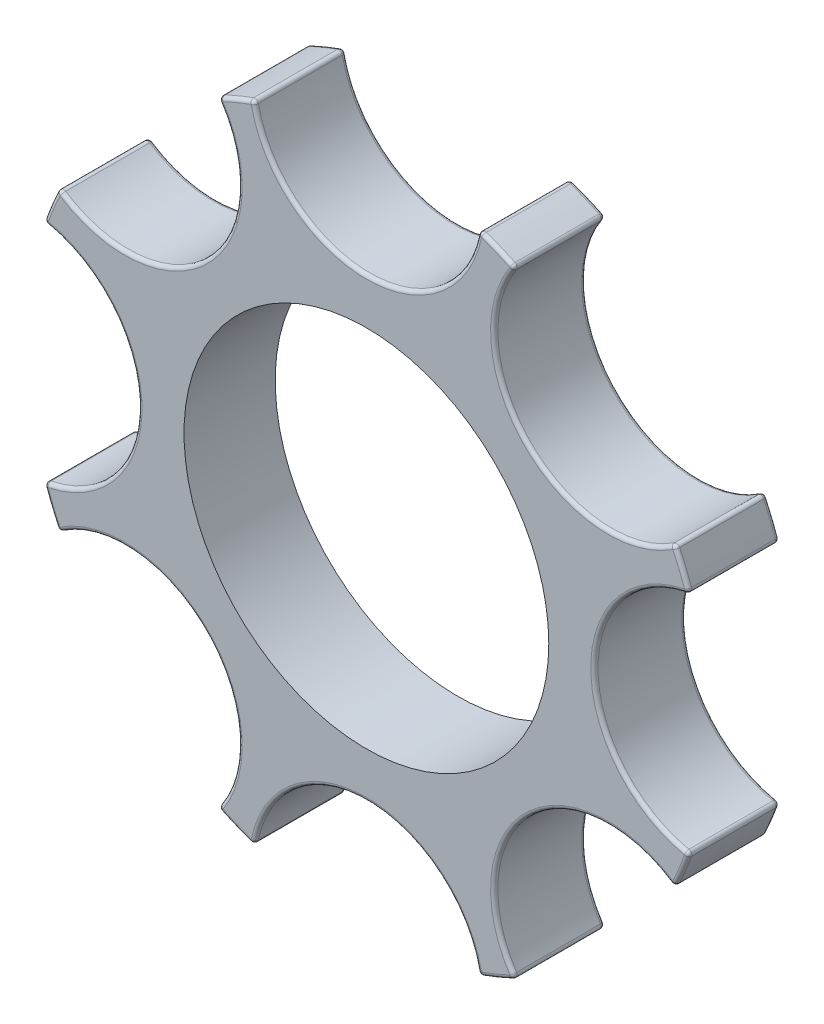
SolidWorks part; units mm, degrees
material "Plain Carbon Steel"
ref_plane "Front Plane" through (0, 0, 0) normal (0, 0, 1) x (1, 0, 0)
ref_plane "Top Plane" through (0, 0, 0) normal (0, 1, 0) x (1, 0, 0)
ref_plane "Right Plane" through (0, 0, 0) normal (1, 0, 0) x (0, 0, -1)
sketch "Sketch1" plane through (0, 0, 0) normal (0, 0, 1) x (1, 0, 0)
  circle A0 centre (0, 0) radius 10.16
  arc A1 (-17.1494, 8.2947) -> (-17.9917, 6.2612) centre (0, 0) ccw
  arc A2 (-6.2612, 17.9917) -> (6.2612, 17.9917) centre (0, 19.05) ccw
  arc A3 (-17.1494, 8.2947) -> (-17.9917, 6.2612) centre (0, 0) ccw
  arc A4 (8.2947, 17.1494) -> (17.1494, 8.2947) centre (13.4704, 13.4704) ccw
  arc A5 (-17.1494, 8.2947) -> (-17.9917, 6.2612) centre (0, 0) ccw
  arc A6 (17.9917, 6.2612) -> (17.9917, -6.2612) centre (19.05, 0) ccw
  arc A7 (-17.1494, 8.2947) -> (-17.9917, 6.2612) centre (0, 0) ccw
  arc A8 (17.1494, -8.2947) -> (8.2947, -17.1494) centre (13.4704, -13.4704) ccw
  arc A9 (-17.1494, 8.2947) -> (-17.9917, 6.2612) centre (0, 0) ccw
  arc A10 (6.2612, -17.9917) -> (-6.2612, -17.9917) centre (0, -19.05) ccw
  arc A11 (-17.1494, 8.2947) -> (-17.9917, 6.2612) centre (0, 0) ccw
  arc A12 (-8.2947, -17.1494) -> (-17.1494, -8.2947) centre (-13.4704, -13.4704) ccw
  arc A13 (-17.1494, 8.2947) -> (-17.9917, 6.2612) centre (0, 0) ccw
  arc A14 (-17.9917, -6.2612) -> (-17.9917, 6.2612) centre (-19.05, 0) ccw
  arc A15 (-17.1494, 8.2947) -> (-17.9917, 6.2612) centre (0, 0) ccw
  arc A16 (-17.1494, 8.2947) -> (-8.2947, 17.1494) centre (-13.4704, 13.4704) ccw
  arc A17 (-6.2612, 17.9917) -> (-8.2947, 17.1494) centre (0, 0) ccw
  arc A18 (-6.2612, 17.9917) -> (-8.2947, 17.1494) centre (0, 0) ccw
  arc A19 (-6.2612, 17.9917) -> (-8.2947, 17.1494) centre (0, 0) ccw
  arc A20 (-6.2612, 17.9917) -> (-8.2947, 17.1494) centre (0, 0) ccw
  arc A21 (-6.2612, 17.9917) -> (-8.2947, 17.1494) centre (0, 0) ccw
  arc A22 (-6.2612, 17.9917) -> (-8.2947, 17.1494) centre (0, 0) ccw
  arc A23 (-6.2612, 17.9917) -> (-8.2947, 17.1494) centre (0, 0) ccw
  arc A24 (-6.2612, 17.9917) -> (-8.2947, 17.1494) centre (0, 0) ccw
  arc A25 (8.2947, 17.1494) -> (6.2612, 17.9917) centre (0, 0) ccw
  arc A26 (8.2947, 17.1494) -> (6.2612, 17.9917) centre (0, 0) ccw
  arc A27 (8.2947, 17.1494) -> (6.2612, 17.9917) centre (0, 0) ccw
  arc A28 (8.2947, 17.1494) -> (6.2612, 17.9917) centre (0, 0) ccw
  arc A29 (8.2947, 17.1494) -> (6.2612, 17.9917) centre (0, 0) ccw
  arc A30 (8.2947, 17.1494) -> (6.2612, 17.9917) centre (0, 0) ccw
  arc A31 (8.2947, 17.1494) -> (6.2612, 17.9917) centre (0, 0) ccw
  arc A32 (8.2947, 17.1494) -> (6.2612, 17.9917) centre (0, 0) ccw
  arc A33 (17.9917, 6.2612) -> (17.1494, 8.2947) centre (0, 0) ccw
  arc A34 (17.9917, 6.2612) -> (17.1494, 8.2947) centre (0, 0) ccw
  arc A35 (17.9917, 6.2612) -> (17.1494, 8.2947) centre (0, 0) ccw
  arc A36 (17.9917, 6.2612) -> (17.1494, 8.2947) centre (0, 0) ccw
  arc A37 (17.9917, 6.2612) -> (17.1494, 8.2947) centre (0, 0) ccw
  arc A38 (17.9917, 6.2612) -> (17.1494, 8.2947) centre (0, 0) ccw
  arc A39 (17.9917, 6.2612) -> (17.1494, 8.2947) centre (0, 0) ccw
  arc A40 (17.9917, 6.2612) -> (17.1494, 8.2947) centre (0, 0) ccw
  arc A41 (17.1494, -8.2947) -> (17.9917, -6.2612) centre (0, 0) ccw
  arc A42 (17.1494, -8.2947) -> (17.9917, -6.2612) centre (0, 0) ccw
  arc A43 (17.1494, -8.2947) -> (17.9917, -6.2612) centre (0, 0) ccw
  arc A44 (17.1494, -8.2947) -> (17.9917, -6.2612) centre (0, 0) ccw
  arc A45 (17.1494, -8.2947) -> (17.9917, -6.2612) centre (0, 0) ccw
  arc A46 (17.1494, -8.2947) -> (17.9917, -6.2612) centre (0, 0) ccw
  arc A47 (17.1494, -8.2947) -> (17.9917, -6.2612) centre (0, 0) ccw
  arc A48 (17.1494, -8.2947) -> (17.9917, -6.2612) centre (0, 0) ccw
  arc A49 (6.2612, -17.9917) -> (8.2947, -17.1494) centre (0, 0) ccw
  arc A50 (6.2612, -17.9917) -> (8.2947, -17.1494) centre (0, 0) ccw
  arc A51 (6.2612, -17.9917) -> (8.2947, -17.1494) centre (0, 0) ccw
  arc A52 (6.2612, -17.9917) -> (8.2947, -17.1494) centre (0, 0) ccw
  arc A53 (6.2612, -17.9917) -> (8.2947, -17.1494) centre (0, 0) ccw
  arc A54 (6.2612, -17.9917) -> (8.2947, -17.1494) centre (0, 0) ccw
  arc A55 (6.2612, -17.9917) -> (8.2947, -17.1494) centre (0, 0) ccw
  arc A56 (6.2612, -17.9917) -> (8.2947, -17.1494) centre (0, 0) ccw
  arc A57 (-8.2947, -17.1494) -> (-6.2612, -17.9917) centre (0, 0) ccw
  arc A58 (-8.2947, -17.1494) -> (-6.2612, -17.9917) centre (0, 0) ccw
  arc A59 (-8.2947, -17.1494) -> (-6.2612, -17.9917) centre (0, 0) ccw
  arc A60 (-8.2947, -17.1494) -> (-6.2612, -17.9917) centre (0, 0) ccw
  arc A61 (-8.2947, -17.1494) -> (-6.2612, -17.9917) centre (0, 0) ccw
  arc A62 (-8.2947, -17.1494) -> (-6.2612, -17.9917) centre (0, 0) ccw
  arc A63 (-8.2947, -17.1494) -> (-6.2612, -17.9917) centre (0, 0) ccw
  arc A64 (-8.2947, -17.1494) -> (-6.2612, -17.9917) centre (0, 0) ccw
  arc A65 (-17.9917, -6.2612) -> (-17.1494, -8.2947) centre (0, 0) ccw
  arc A66 (-17.9917, -6.2612) -> (-17.1494, -8.2947) centre (0, 0) ccw
  arc A67 (-17.9917, -6.2612) -> (-17.1494, -8.2947) centre (0, 0) ccw
  arc A68 (-17.9917, -6.2612) -> (-17.1494, -8.2947) centre (0, 0) ccw
  arc A69 (-17.9917, -6.2612) -> (-17.1494, -8.2947) centre (0, 0) ccw
  arc A70 (-17.9917, -6.2612) -> (-17.1494, -8.2947) centre (0, 0) ccw
  arc A71 (-17.9917, -6.2612) -> (-17.1494, -8.2947) centre (0, 0) ccw
  arc A72 (-17.9917, -6.2612) -> (-17.1494, -8.2947) centre (0, 0) ccw
  point P29 (0, 0)
  dimension "D1" = 20.32
  dimension "D2" = 38.1
  dimension "D3" = 12.7
  dimension "D4" = 8
extrude "Boss-Extrude1" add sketch "Sketch1" along normal blind 5.08 contours A14 A65 A12 A57 A10 A49 A8 A41 A6 A33 A4 A25 A2 A17 A16 A1 A0
fillet "Fillet1" radius 0.2032 48 edges at (8.9803, 8.9803, 5.08) (8.9803, 8.9803, 0) (-8.9803, 8.9803, 5.08) (-8.9803, 8.9803, 0) (0, 12.7, 5.08) (0, 12.7, 0) (8.2947, 17.1494, 2.54) (17.1494, 8.2947, 2.54) (7.2901, 17.5999, 5.08) (-6.2612, 17.9917, 2.54) (6.2612, 17.9917, 2.54) (7.2901, 17.5999, 0) (-7.2901, 17.5999, 5.08) (-17.1494, 8.2947, 2.54) (-8.2947, 17.1494, 2.54) (-7.2901, 17.5999, 0) (12.7, 0, 5.08) (12.7, 0, 0) (8.9803, -8.9803, 5.08) (8.9803, -8.9803, 0) (0, -12.7, 5.08) (0, -12.7, 0) (-8.9803, -8.9803, 5.08) (-8.9803, -8.9803, 0) (-12.7, 0, 5.08) (-12.7, 0, 0) (-17.5999, 7.2901, 5.08) (-17.9917, -6.2612, 2.54) (-17.9917, 6.2612, 2.54) (-17.5999, 7.2901, 0) (-17.5999, -7.2901, 5.08) (-8.2947, -17.1494, 2.54) (-17.1494, -8.2947, 2.54) (-17.5999, -7.2901, 0) (-7.2901, -17.5999, 5.08) (6.2612, -17.9917, 2.54) (-6.2612, -17.9917, 2.54) (-7.2901, -17.5999, 0) (7.2901, -17.5999, 5.08) (17.1494, -8.2947, 2.54) (8.2947, -17.1494, 2.54) (7.2901, -17.5999, 0) (17.5999, -7.2901, 5.08) (17.9917, 6.2612, 2.54) (17.9917, -6.2612, 2.54) (17.5999, -7.2901, 0) (17.5999, 7.2901, 5.08) (17.5999, 7.2901, 0)
